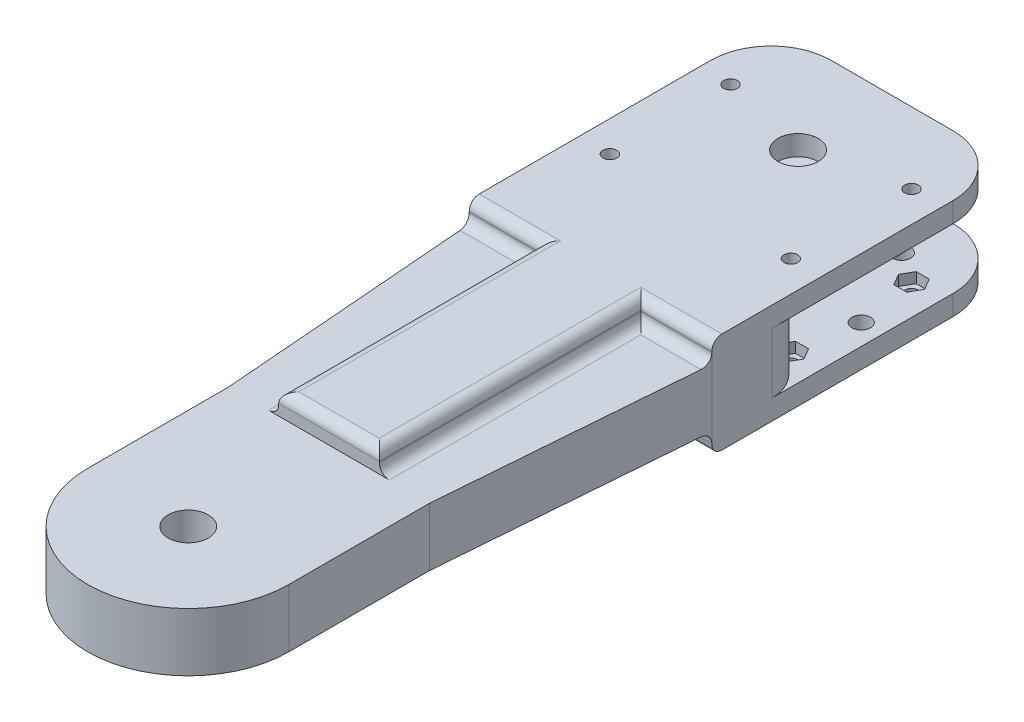
SolidWorks part; units mm, degrees
ref_plane "Front Plane" through (0, 0, 0) normal (0, 0, 1) x (1, 0, 0)
ref_plane "Top Plane" through (0, 0, 0) normal (0, 1, 0) x (1, 0, 0)
ref_plane "Right Plane" through (0, 0, 0) normal (1, 0, 0) x (0, 0, -1)
sketch "Sketch2" plane through (0, 0, 0) normal (0, 1, 0) x (1, 0, 0)
  line L0 (0, 32.7) -> (0, -32.7) construction
  line L1 (15.15, -32.7) -> (-15.15, -32.7)
  line L2 (30.15, -17.7) -> (30.15, 17.7)
  line L3 (15.15, 32.7) -> (-15.15, 32.7)
  line L4 (-30.15, -17.7) -> (-30.15, 17.7)
  line L5 (30.15, -32.7) -> (-30.15, 32.7) construction
  line L6 (30.15, 32.7) -> (-30.15, -32.7) construction
  line L7 (30.15, 0) -> (-30.15, 0) construction
  line L8 (-15, 20) -> (-15, -20) construction
  line L9 (-22.5, 15) -> (-22.5, -15) construction
  line L10 (-15, 20) -> (15, 20) construction
  line L12 (-9, 4.7163) -> (-9, -16.9)
  line L13 (-9, -16.9) -> (9, -16.9)
  line L14 (9, 4.7163) -> (9, -16.9)
  line L15 (-9, 4.7163) -> (9, -16.9) construction
  line L16 (-9, -16.9) -> (9, 4.7163) construction
  line L17 (0, 19.4) -> (0, -16.9) construction
  arc A0 (15.15, -32.7) -> (30.15, -17.7) centre (15.15, -17.7) ccw
  arc A1 (-15.15, -32.7) -> (-30.15, -17.7) centre (-15.15, -17.7) cw
  arc A2 (-15.15, 32.7) -> (-30.15, 17.7) centre (-15.15, 17.7) ccw
  arc A3 (30.15, 17.7) -> (15.15, 32.7) centre (15.15, 17.7) ccw
  circle A4 centre (-15, 20) radius 2.3
  circle A5 centre (-25, 0) radius 2.3
  circle A6 centre (-15, -20) radius 2.3
  circle A7 centre (-22.5, -15) radius 1.7
  circle A8 centre (-22.5, 15) radius 1.7
  circle A9 centre (15, 20) radius 2.3
  circle A10 centre (22.5, 15) radius 1.7
  circle A11 centre (25, 0) radius 2.3
  circle A12 centre (22.5, -15) radius 1.7
  circle A13 centre (15, -20) radius 2.3
  arc A14 (9, 4.7163) -> (-9, 4.7163) centre (0, 9.3) ccw
  point P0 (0, 0)
  point P33 (0, -6.0918)
  point P36 (-15, 0)
  point P37 (-22.5, 0)
  dimension "D3" = 15
  dimension "D4" = 4.6
  dimension "D5" = 4.6
  dimension "D6" = 4.6
  dimension "D7" = 3.4
  dimension "D8" = 3.4
  dimension "D14" = 20.2
  dimension "D1" = 60.3
  dimension "D2" = 65.4
  dimension "D9" = 15
  dimension "D10" = 22.5
  dimension "D11" = 25
  dimension "D12" = 20
  dimension "D13" = 15
  dimension "D15" = 36.3
  dimension "D16" = 18
  dimension "D17" = 0.6
extrude "Boss-Extrude1" add sketch "Sketch2" along normal blind 5
sketch "Sketch3" plane through (0, 0, 0) normal (0, -1, 0) x (1, 0, 0)
  line L0 (-30.15, 17.7) -> (-30.15, 42.3)
  line L1 (-30.15, 42.3) -> (30.15, 42.3)
  line L2 (30.15, 42.3) -> (30.15, 17.7)
  line L3 (30.15, 17.7) -> (30.15, -17.7) construction
  line L4 (30.15, 17.7) -> (15.15, 32.7)
  line L5 (15.15, 32.7) -> (-15.15, 32.7)
  line L6 (-15.15, 32.7) -> (-30.15, 17.7)
  line L7 (15.15, -32.7) -> (-15.15, -32.7) construction
  dimension "D1" = 75
extrude "Boss-Extrude2" add sketch "Sketch3" against normal blind 5
sketch "Sketch4" plane through (0, 5, 0) normal (0, 1, 0) x (1, 0, 0)
  line L0 (30.15, -42.3) -> (30.15, 17.7) construction
  line L1 (-30.15, -42.3) -> (30.15, -42.3)
  line L2 (-30.15, -42.3) -> (-30.15, -27.3)
  line L3 (-30.15, -27.3) -> (30.15, -27.3)
  line L4 (30.15, -42.3) -> (30.15, -27.3)
  dimension "D1" = 15
extrude "Boss-Extrude3" add sketch "Sketch4" along normal blind 15
sketch "Sketch5" plane through (0, 20, 0) normal (0, 1, 0) x (1, 0, 0)
  line L0 (15.15, 32.7) -> (-15.15, 32.7) construction
  line L1 (-30.15, -42.3) -> (30.15, -42.3)
  line L2 (-30.15, -42.3) -> (-30.15, 17.7)
  line L3 (-15.15, 32.7) -> (15.15, 32.7)
  line L4 (30.15, -42.3) -> (30.15, 17.7)
  line L5 (30.15, -27.3) -> (30.15, 17.7) construction
  arc A0 (-30.15, 17.7) -> (-15.15, 32.7) centre (-15.15, 17.7) cw
  arc A1 (15.15, 32.7) -> (30.15, 17.7) centre (15.15, 17.7) cw
  circle A2 centre (-22.5, 15) radius 1.7
  circle A3 centre (-22.5, -15) radius 1.7
  circle A4 centre (22.5, 15) radius 1.7
  circle A5 centre (22.5, -15) radius 1.7
  circle A6 centre (0, 9.3) radius 5
  dimension "D1" = 15
  dimension "D2" = 3.4
  dimension "D3" = 3.4
  dimension "D4" = 3.4
  dimension "D5" = 3.4
  dimension "D6" = 10
extrude "Boss-Extrude4" add sketch "Sketch5" along normal blind 5
sketch "Sketch6" plane through (0, 0, 27.3) normal (0, 0, -1) x (-1, 0, 0)
  line L1 (-30.15, 20) -> (30.15, 20)
  line L2 (-30.15, 20) -> (-30.15, 5)
  line L3 (-30.15, 5) -> (30.15, 5)
  line L4 (30.15, 20) -> (30.15, 5)
extrude "Boss-Extrude5" add sketch "Sketch6" along normal blind 10
fillet "Fillet1" radius 10 2 edges at (-30.15, 12.5, 17.3) (30.15, 12.5, 17.3)
sketch "Sketch7" plane through (0, 5, 0) normal (0, 1, 0) x (1, 0, 0)
  line L0 (0, 0) -> (0, -21.4683) construction
  line L1 (25.7332, -15) -> (24.1166, -12.2)
  line L2 (24.1166, -12.2) -> (20.8834, -12.2)
  line L3 (20.8834, -12.2) -> (19.2668, -15)
  line L4 (19.2668, -15) -> (20.8834, -17.8)
  line L5 (20.8834, -17.8) -> (24.1166, -17.8)
  line L6 (24.1166, -17.8) -> (25.7332, -15)
  line L7 (0, 0) -> (16.3121, 0) construction
  line L8 (-24.1166, -17.8) -> (-25.7332, -15)
  line L9 (-20.8834, -17.8) -> (-24.1166, -17.8)
  line L10 (-20.8834, -12.2) -> (-19.2668, -15)
  line L11 (-24.1166, -12.2) -> (-20.8834, -12.2)
  line L12 (-25.7332, -15) -> (-24.1166, -12.2)
  line L13 (-19.2668, -15) -> (-20.8834, -17.8)
  line L14 (-19.2668, 15) -> (-20.8834, 17.8)
  line L15 (-25.7332, 15) -> (-24.1166, 12.2)
  line L16 (-24.1166, 12.2) -> (-20.8834, 12.2)
  line L17 (-20.8834, 12.2) -> (-19.2668, 15)
  line L18 (-20.8834, 17.8) -> (-24.1166, 17.8)
  line L19 (-24.1166, 17.8) -> (-25.7332, 15)
  line L20 (24.1166, 17.8) -> (25.7332, 15)
  line L21 (20.8834, 17.8) -> (24.1166, 17.8)
  line L22 (19.2668, 15) -> (20.8834, 17.8)
  line L23 (20.8834, 12.2) -> (19.2668, 15)
  line L24 (24.1166, 12.2) -> (20.8834, 12.2)
  line L25 (25.7332, 15) -> (24.1166, 12.2)
  circle A0 centre (22.5, -15) radius 2.8 construction
  dimension "D1" = 5.6
  dimension "D2" = 2.8
extrude "Cut-Extrude1" cut sketch "Sketch7" against normal blind 2.6 and the other way blind 2.7
sketch "Sketch8" plane through (0, 20, 0) normal (0, -1, 0) x (1, 0, 0)
  line L0 (0, 0) -> (0, 12.2) construction
  line L1 (25.7332, 15) -> (24.1166, 17.8)
  line L2 (24.1166, 17.8) -> (20.8834, 17.8)
  line L3 (20.8834, 17.8) -> (19.2668, 15)
  line L4 (19.2668, 15) -> (20.8834, 12.2)
  line L5 (20.8834, 12.2) -> (24.1166, 12.2)
  line L6 (24.1166, 12.2) -> (25.7332, 15)
  line L7 (0, 0) -> (13.3782, 0) construction
  line L8 (-24.1166, 12.2) -> (-25.7332, 15)
  line L9 (-20.8834, 12.2) -> (-24.1166, 12.2)
  line L10 (-19.2668, 15) -> (-20.8834, 12.2)
  line L11 (-20.8834, 17.8) -> (-19.2668, 15)
  line L12 (-24.1166, 17.8) -> (-20.8834, 17.8)
  line L13 (-25.7332, 15) -> (-24.1166, 17.8)
  line L14 (-25.7332, -15) -> (-24.1166, -17.8)
  line L15 (-24.1166, -17.8) -> (-20.8834, -17.8)
  line L16 (-20.8834, -17.8) -> (-19.2668, -15)
  line L17 (-19.2668, -15) -> (-20.8834, -12.2)
  line L18 (-20.8834, -12.2) -> (-24.1166, -12.2)
  line L19 (-24.1166, -12.2) -> (-25.7332, -15)
  line L20 (24.1166, -12.2) -> (25.7332, -15)
  line L21 (20.8834, -12.2) -> (24.1166, -12.2)
  line L22 (19.2668, -15) -> (20.8834, -12.2)
  line L23 (20.8834, -17.8) -> (19.2668, -15)
  line L24 (24.1166, -17.8) -> (20.8834, -17.8)
  line L25 (25.7332, -15) -> (24.1166, -17.8)
  circle A0 centre (22.5, 15) radius 2.8 construction
  dimension "D1" = 5.6
  dimension "D2" = 2.8
extrude "Cut-Extrude2" cut sketch "Sketch8" against normal blind 2.6 and the other way blind 2.7
sketch "Sketch9" plane through (0, 0, 42.3) normal (0, 0, 1) x (1, 0, 0)
  line L1 (-12.5, 25) -> (12.5, 25)
  line L2 (-12.5, 25) -> (-12.5, 0)
  line L3 (-12.5, 0) -> (12.5, 0)
  line L4 (12.5, 25) -> (12.5, 0)
  point P6 (0, 0)
  dimension "D1" = 25
extrude "Boss-Extrude6" add sketch "Sketch9" along normal blind 65
ref_plane "Plane1" through (0, 5.25, 0) normal (0, 1, 0) x (1, 0, 0)
sketch "Sketch11" plane through (0, 5.25, 0) normal (0, 1, 0) x (1, 0, 0)
  line L0 (-25, -142.3) -> (-25, -107.3)
  line L1 (-25, -107.3) -> (25, -107.3)
  line L2 (25, -107.3) -> (25, -142.3)
  line L3 (0, -142.3) -> (0, -127.3) construction
  line L4 (3.75, -135.8) -> (-3.75, -135.8) construction
  line L5 (-3.75, -135.8) -> (-2.4745, -126.9436)
  line L6 (3.75, -135.8) -> (2.4745, -126.9436)
  line L7 (3.7542, -135.8024) -> (12.0618, -132.4789)
  line L8 (7.5042, -142.2976) -> (14.5363, -136.7648)
  line L9 (7.5042, -142.3024) -> (14.5363, -147.8352)
  line L10 (3.7542, -148.7976) -> (12.0618, -152.1211)
  line L11 (3.75, -148.8) -> (2.4745, -157.6564)
  line L12 (-3.75, -148.8) -> (-2.4745, -157.6564)
  line L13 (-3.7542, -148.7976) -> (-12.0618, -152.1211)
  line L14 (-7.5042, -142.3024) -> (-14.5363, -147.8352)
  line L15 (-7.5042, -142.2976) -> (-14.5363, -136.7648)
  line L16 (-3.7542, -135.8024) -> (-12.0618, -132.4789)
  line L17 (-7.5042, -142.2976) -> (-7.5042, -142.3024)
  line L18 (-3.7542, -135.8024) -> (-3.75, -135.8)
  line L19 (3.75, -135.8) -> (3.7542, -135.8024)
  line L20 (7.5042, -142.2976) -> (7.5042, -142.3024)
  line L21 (3.75, -148.8) -> (3.7542, -148.7976)
  line L22 (-3.75, -148.8) -> (-3.7542, -148.7976)
  line L23 (12.5, -107.3) -> (-12.5, -107.3) construction
  line L26 (-12.5, -107.3) -> (12.5, -107.3) construction
  arc A0 (-25, -142.3) -> (25, -142.3) centre (0, -142.3) ccw
  arc A1 (2.4745, -126.9436) -> (-2.4745, -126.9436) centre (0, -127.3) ccw
  arc A2 (14.5363, -136.7648) -> (12.0618, -132.4789) centre (12.9904, -134.8) ccw
  arc A3 (12.0618, -152.1211) -> (14.5363, -147.8352) centre (12.9904, -149.8) ccw
  arc A4 (-2.4745, -157.6564) -> (2.4745, -157.6564) centre (0, -157.3) ccw
  arc A5 (-14.5363, -147.8352) -> (-12.0618, -152.1211) centre (-12.9904, -149.8) ccw
  arc A6 (-12.0618, -132.4789) -> (-14.5363, -136.7648) centre (-12.9904, -134.8) ccw
  point P9 (0, -135.8)
  point P39 (0, -142.3)
  point P43 (0, -107.3)
  point P44 (0, -107.3)
  dimension "D1" = 50
  dimension "D5" = 5
  dimension "D2" = 35
  dimension "D3" = 7.5
  dimension "D4" = 15
  dimension "D7" = 6.5
  dimension "D6" = 6
extrude "Boss-Extrude7" add sketch "Sketch11" along normal blind 7.25
sketch "Sketch12" plane through (0, 12.5, 0) normal (0, 1, 0) x (1, 0, 0)
  line L0 (-25, -142.3) -> (-25, -107.3)
  line L1 (-25, -107.3) -> (25, -107.3)
  line L2 (25, -107.3) -> (25, -142.3)
  arc A0 (-25, -142.3) -> (25, -142.3) centre (0, -142.3) ccw
  circle A2 centre (0, -142.3) radius 5
  dimension "D1" = 10
extrude "Boss-Extrude8" add sketch "Sketch12" along normal blind 7.25
ref_plane "Plane9" through (0, 12.5, 0) normal (0, 1, 0) x (1, 0, 0)
sketch "Sketch13" plane through (0, 12.5, 0) normal (0, 1, 0) x (1, 0, 0)
  line L0 (30.15, -42.3) -> (25, -107.3)
rib "Rib1" sketch "Sketch13" sketch "Sketch13" thickness 14.5 extrusion direction parallel to sketch draft on no parameters "D1"=14.5
sketch "Sketch14" plane through (0, 12.5, 0) normal (0, 1, 0) x (1, 0, 0)
  line L0 (-30.15, -42.3) -> (-25, -107.3)
rib "Rib2" sketch "Sketch14" sketch "Sketch14" thickness 14.5 extrusion direction parallel to sketch draft on no parameters "D1"=14.5
fillet "Fillet2" radius 2.5 10 edges at (-21.325, 0, 42.3) (-12.5, 0, 74.8) (0, 0, 107.3) (12.5, 0, 74.8) (21.325, 0, 42.3) (-12.5, 25, 74.8) (0, 25, 107.3) (12.5, 25, 74.8) (-21.325, 25, 42.3) (21.325, 25, 42.3)
fillet "Fillet3" radius 2.5 8 edges at (21.325, 5.25, 42.3) (12.5, 5.25, 74.8) (12.5, 19.75, 74.8) (21.325, 19.75, 42.3) (-12.5, 19.75, 74.8) (-21.325, 5.25, 42.3) (-12.5, 5.25, 74.8) (-21.325, 19.75, 42.3)
